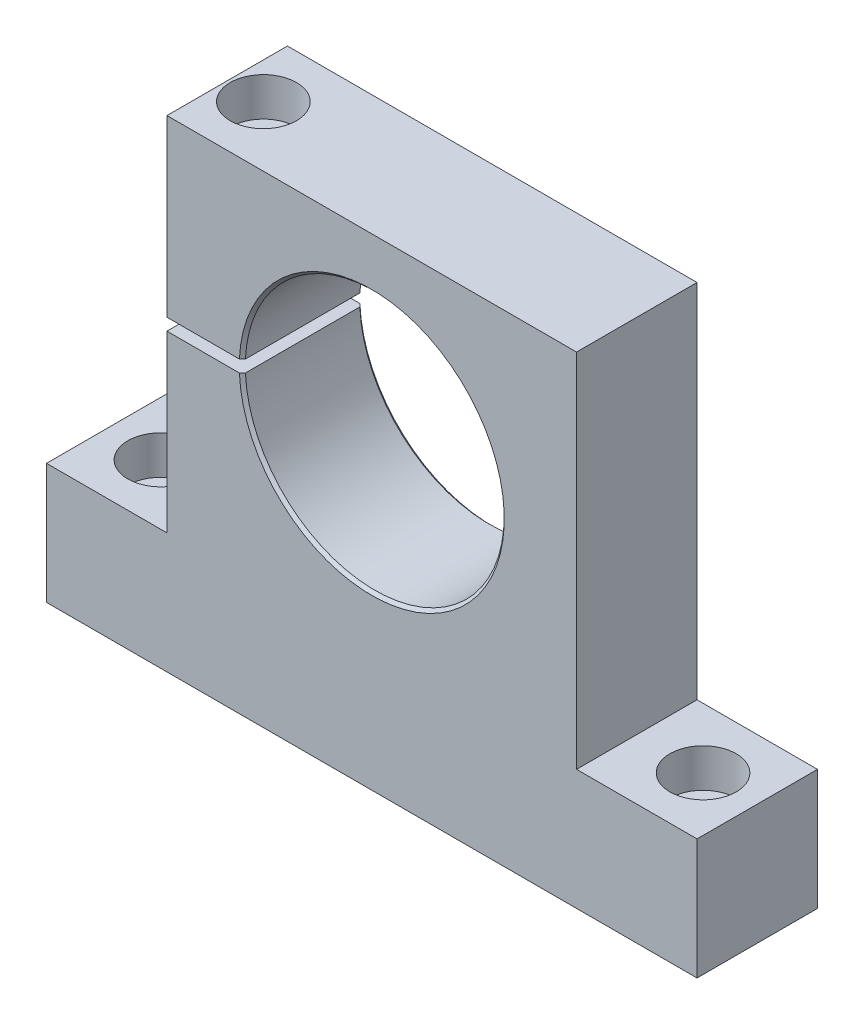
SolidWorks part; units mm, degrees
ref_plane "Piano frontale" through (0, 0, 0) normal (0, 0, 1) x (1, 0, 0)
ref_plane "Piano superiore" through (0, 0, 0) normal (0, 1, 0) x (1, 0, 0)
ref_plane "Piano destro" through (0, 0, 0) normal (1, 0, 0) x (0, 0, -1)
sketch "Schizzo1" plane through (0, 0, 0) normal (0, 0, 1) x (1, 0, 0)
  line L0 (0, 0) -> (108, 0)
  line L1 (0, 0) -> (0, 20)
  line L2 (0, 20) -> (20, 20)
  line L3 (20, 20) -> (20, 80)
  line L4 (20, 80) -> (88, 80)
  line L5 (54, 0) -> (54, 80) construction
  line L6 (108, 20) -> (88, 20)
  line L7 (108, 0) -> (108, 20)
  line L8 (88, 20) -> (88, 80)
  circle A0 centre (54, 50) radius 21.5
  dimension "D4" = 43
  dimension "D1" = 54
  dimension "D2" = 20
  dimension "D3" = 60
  dimension "D5" = 30
  dimension "D6" = 20
extrude "Estrusione-Estrusione1" add sketch "Schizzo1" along normal blind 20
sketch "Schizzo2" plane through (0, 20, 0) normal (0, 1, 0) x (1, 0, 0)
  line L0 (0, -10) -> (108, -10) construction
  line L1 (0, -20) -> (0, 0) construction
  line L2 (108, -20) -> (108, 0) construction
  line L6 (54, 0) -> (54, -20) construction
  line L7 (88, 0) -> (20, 0) construction
  line L8 (88, -20) -> (20, -20) construction
  point P12 (9, -10)
  point P19 (99, -10)
  dimension "D1" = 90
hole_wizard "Foro lamato per Vite M6 a testa cilindrica-1" positions "Schizzo3D2" profile "Schizzo4" counterbore size "M6" standard "ISO" end condition through all
sketch3d "Schizzo3D2"
  point P0 (9, 20, 10)
  point P3 (99, 20, 10)
sketch "Schizzo4" plane through (9, 20, 10) normal (1, 0, 0) x (0, 0, 1)
  line L0 (0, 0) -> (0, 20)
  line L1 (0, 20) -> (3.3, 20)
  line L3 (3.3, 20) -> (3.3, 6.4)
  line L4 (3.3, 6.4) -> (5.5, 6.4)
  line L5 (5.5, 6.4) -> (5.5, 0)
  line L7 (5.5, 0) -> (0, 0)
  line L11 (0, -6.35) -> (0, 107.95) construction
  dimension "Thru Hole Dia." = 6.6
  dimension "Thru Hole Depth" = 20
  dimension "C'Bore Dia." = 11
  dimension "C'Bore Depth" = 6.4
sketch "Schizzo5" plane through (0, 80, 0) normal (0, 1, 0) x (1, 0, 0)
  line L0 (20, -10) -> (80.6806, -10) construction
  line L1 (20, -20) -> (20, 0) construction
  line L2 (0, -10) -> (108, -10) construction
  line L3 (20, -20) -> (20, 0) construction
  point P6 (26, -10)
  dimension "D1" = 6
hole_wizard "CBORE for M6 Hex Socket Head Cap Screw1" positions "Schizzo3D3" profile "Schizzo6" counterbore size "M6" standard "ISO"
sketch3d "Schizzo3D3"
  point P0 (26, 80, 10)
sketch "Schizzo6" plane through (26, 80, 10) normal (1, 0, 0) x (0, 0, 1)
  line L0 (0, 0) -> (0, 51.9828)
  line L1 (0, 51.9828) -> (3.3, 50)
  line L2 (3.3, 50) -> (3.3, 6.4)
  line L3 (3.3, 6.4) -> (5.5, 6.4)
  line L4 (5.5, 6.4) -> (5.5, 0)
  line L5 (5.5, 0) -> (0, 0)
  line L10 (0, 51.9828) -> (-3.3, 50) construction
  line L11 (0, -6.35) -> (0, 107.95) construction
  dimension "Hole Dia." = 6.6
  dimension "Hole Depth" = 50
  dimension "C'Bore Dia." = 11
  dimension "C'Bore Depth" = 6.4
  dimension "Drill Angle" = 118
sketch "Schizzo7" plane through (0, 0, 0) normal (0, 0, -1) x (-1, 0, 0)
  line L0 (-54, 50) -> (-5.4537, 50) construction
  line L2 (-19.9047, 49) -> (-35.4261, 49)
  line L3 (-19.9047, 49) -> (-19.9047, 51)
  line L4 (-19.9047, 51) -> (-35.4261, 51)
  line L5 (-35.4261, 49) -> (-35.4261, 51)
  line L6 (-19.9047, 49) -> (-35.4261, 51) construction
  line L7 (-19.9047, 51) -> (-35.4261, 49) construction
  point P3 (-27.6654, 50)
  dimension "D1" = 2
extrude "Taglio-Estrusione1" cut sketch "Schizzo7" against normal through all
chamfer "Chamfer1" distance 0.5 angle 45 1 edges at (75.5, 50, 0)
chamfer "Chamfer2" distance 0.5 angle 45 1 edges at (75.5, 50, 20)
